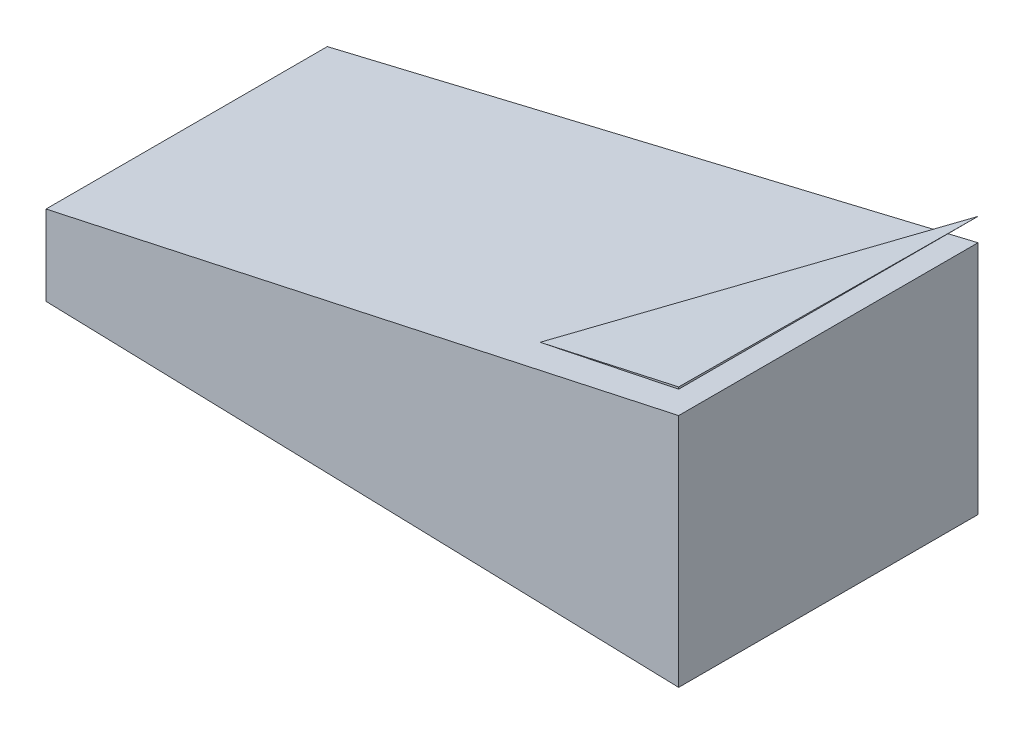
SolidWorks part; units mm, degrees
ref_plane "Front Plane" through (0, 0, 0) normal (0, 0, 1) x (1, 0, 0)
ref_plane "Top Plane" through (0, 0, 0) normal (0, 1, 0) x (1, 0, 0)
ref_plane "Right Plane" through (0, 0, 0) normal (1, 0, 0) x (0, 0, -1)
sketch "Sketch1" plane through (0, 0, 0) normal (0, 1, 0) x (1, 0, 0)
  line L1 (0, 0) -> (76.2, 0)
  line L2 (0, 0) -> (0, 50.8)
  line L3 (0, 50.8) -> (76.2, 50.8)
  line L4 (76.2, 0) -> (76.2, 50.8)
  dimension "D1" = 50.8
  dimension "D2" = 76.2
extrude "Boss-Extrude1" add sketch "Sketch1" along normal blind 30.48
sketch "Sketch3" plane through (0, 30.48, 0) normal (0, 1, 0) x (1, 0, 0)
  line L0 (0, 17.8514) -> (76.2, 15.7424)
  line L1 (0, 50.8) -> (0, 0) construction
  line L2 (76.2, 0) -> (76.2, 50.8) construction
  line L3 (76.2, 15.7424) -> (76.2, 0)
  line L4 (76.2, 0) -> (0, 0)
  line L5 (0, 0) -> (0, 17.8514)
extrude "Cut-Extrude2" cut sketch "Sketch3" against normal through all
sketch "Sketch4" plane through (0.4937, 0, -17.8378) normal (-0.0277, 0, 0.9996) x (0.9996, 0, 0.0277)
  line L0 (75.7353, 30.48) -> (-0.4939, 11.992)
  line L1 (-0.4939, 0) -> (-0.4939, 30.48) construction
  line L2 (-0.4939, 11.992) -> (-0.4939, 30.48)
  line L3 (75.7353, 30.48) -> (-0.4939, 30.48) construction
  line L4 (-0.4939, 30.48) -> (75.7353, 30.48)
extrude "Cut-Extrude3" cut sketch "Sketch4" against normal through all
sketch "Sketch6" plane through (0, 0, -50.8) normal (0, 0, -1) x (-1, 0, 0)
  line L0 (0, 9.3671) -> (-76.2, 27.5723)
  line L1 (0, 30.48) -> (0, 0) construction
  line L2 (-76.2, 30.2448) -> (-76.2, 0) construction
  line L3 (-76.2, 27.5723) -> (-76.2, 30.2448)
  line L4 (-0.9119, 11.992) -> (-76.2, 30.2448) construction
  line L7 (-0.9119, 32.3121) -> (0, 32.3121)
  line L8 (0, 32.3121) -> (0, 9.3671)
  line L9 (-76.2, 30.2448) -> (-0.9119, 13.0397)
  line L10 (-0.9119, 13.0397) -> (-0.9119, 32.3121)
extrude "Cut-Extrude7" cut sketch "Sketch6" against normal through all
